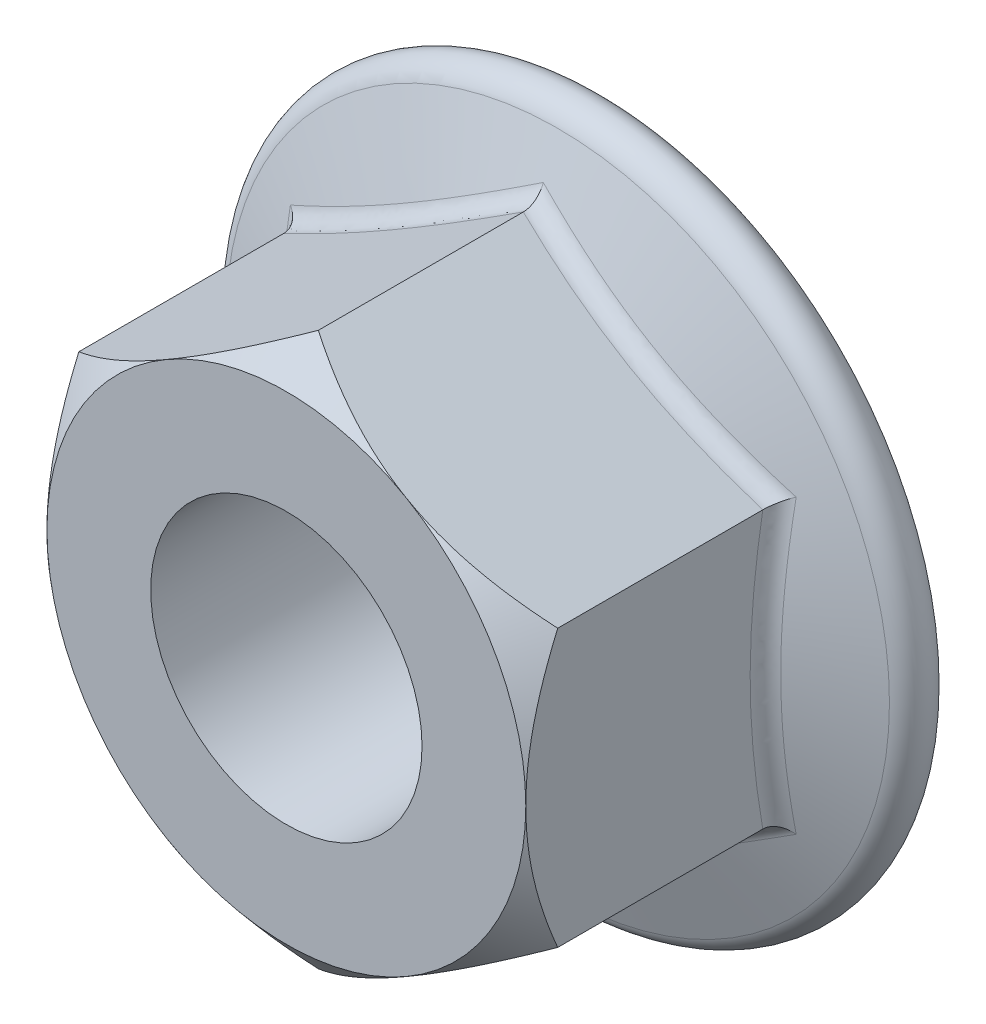
SolidWorks part; units mm, degrees
extrude "BaseNut" add sketch "BaseNutSke" against normal blind 10
sketch "BaseNutSke" plane through (0, 0, 0) normal (0, 0, 1) x (1, 0, 0)
  line L6 (7.5, 4.3301) -> (7.5, -4.3301)
  line L7 (-7.5, 4.3301) -> (-7.5, -4.3301)
  line L8 (7.5, 4.3301) -> (0, 8.6603)
  line L9 (0, 8.6603) -> (-7.5, 4.3301)
  line L10 (-7.5, -4.3301) -> (0, -8.6603)
  line L11 (0, -8.6603) -> (7.5, -4.3301)
  circle A0 centre (0, 0) radius 4.25
  dimension "Tap_drill" = 8.5
  dimension "Width_flats" = 15
  dimension "D2" = 7.5
  dimension "D3" = 7.5
  dimension "D1" = 120
  dimension "D4" = 7.5
cosmetic thread "ThreadCosmetic" parameters "Thread_major"=10
pattern_linear "ThdSchPat" [suppressed]
revolve "ThreadSchematic" [suppressed] cut sketch "ThdSchSke" angle 360 about L6
sketch "ThdSchSke" plane through (0, 0, 0) normal (0, 1, 0) x (1, 0, 0)
  line L0 (-5, 0.0254) -> (-4.25, 0.5506)
  line L1 (-4.25, 0.5506) -> (-2.125, 0.5506)
  line L2 (-2.125, 0.5506) -> (-2.125, -0.4998)
  line L3 (-2.125, -0.4998) -> (-4.25, -0.4998)
  line L4 (-4.25, -0.4998) -> (-5, 0.0254)
  line L5 (-3.175, 1.5) -> (3.175, 1.5) construction
  line L6 (0, 1.5) -> (0, -2.9874) construction
  line L7 (0, 10) -> (0, 0) construction
  dimension "Thread_major" = 10
  dimension "SideAngle" = 55
  dimension "Advance" = 1.5
  dimension "D1" = 0.0254
material "AISI 316 Нержавеющая сталь, лист (SS)"
ref_plane "Plane1" through (0, 0, 0) normal (0, 0, 1) x (1, 0, 0)
ref_plane "Plane2" through (0, 0, 0) normal (0, 1, 0) x (1, 0, 0)
ref_plane "Plane3" through (0, 0, 0) normal (1, 0, 0) x (0, 0, -1)
other "Configuration Table"
sketch "Sketch6" plane through (0, 0, 0) normal (1, 0, 0) x (0, 0, -1)
  line L0 (6.2648, 4.25) -> (8.5, 10.3912)
  line L1 (10, 4.25) -> (10, 10.1267)
  line L2 (8.5, 32.2909) -> (8.5, 10.3912) construction
  line L3 (23.7075, 10.9) -> (19.5103, 10.9) construction
  line L4 (10, 4.25) -> (6.2648, 4.25)
  line L5 (23.7075, -10.9) -> (19.5103, -10.9) construction
  line L6 (10, 4.3301) -> (10, 8.6603) construction
  line L7 (0, 0) -> (32.9582, 0) construction
  line L8 (10, -4.25) -> (6.2648, -4.25) construction
  line L9 (10, 0) -> (0, 0) construction
  arc A0 (10, 10.1267) -> (8.5, 10.3912) centre (9.2267, 10.1267) ccw
  dimension "Flange_thickness" = 1.5
  dimension "Flange_dia" = 21.8
  dimension "D2" = 20
  dimension "D1" = 8.5
revolve "Flange" add sketch "Sketch6" angle 360 about L7
sketch "Sketch3" plane through (0, 0, 0) normal (1, 0, 0) x (0, 0, -1)
  line L0 (10, 7.5) -> (9, 8.6603) construction
  line L1 (9, 8.6603) -> (9, 21.3603) construction
  line L2 (9, 21.3603) -> (22.7, 21.3603) construction
  line L3 (22.7, 21.3603) -> (22.7, 7.5) construction
  line L4 (22.7, 7.5) -> (10, 7.5) construction
  line L5 (10, 4.3301) -> (10, 8.6603) construction
  line L6 (7.87, 8.6603) -> (0, 8.6603) construction
  line L7 (0, 0) -> (38.6776, 0) construction
  line L8 (10, 0) -> (0, 0) construction
  line L9 (5, 8.6603) -> (5, 44.222) construction
  line L10 (1, 21.3603) -> (-12.7, 21.3603)
  line L11 (-12.7, 21.3603) -> (-12.7, 7.5)
  line L12 (-12.7, 7.5) -> (0, 7.5)
  line L13 (0, 7.5) -> (1, 8.6603)
  line L14 (1, 8.6603) -> (1, 21.3603)
  line L16 (7.87, 8.6603) -> (0, 8.6603) construction
  dimension "D2" = 1
  dimension "D4" = 12.7
  dimension "D3" = 12.7
  dimension "D5" = 5
revolve "Double-Chamfer" cut sketch "Sketch3" angle 360 about L7
fillet "FlangeFillet" radius 0.6 6 edges
sketch "Sketch5" plane through (0, 0, 0) normal (1, 0, 0) x (0, 0, -1)
  line L0 (35.3492, 5) -> (34.7715, 4.175)
  line L1 (35.4, 5) -> (35.3492, 5)
  line L2 (35.4, 5) -> (35.4, 4.175)
  line L3 (35.4, 4.175) -> (34.7715, 4.175)
  line L6 (-50.8, 5) -> (-50.7492, 5)
  line L7 (-50.7492, 5) -> (-50.1715, 4.175)
  line L9 (-50.1715, 4.175) -> (-50.8, 4.175)
  line L10 (-50.8, 4.175) -> (-50.8, 5)
  line L11 (25.0375, 0) -> (38.388, 0) construction
  line L12 (10, 0) -> (0, 0) construction
  dimension "D1" = 35
  dimension "ThreadMajor" = 5
  dimension "Offset1" = 35.4
revolve "EndChamfer" [suppressed] cut sketch "Sketch5" angle 360 about L11
equation "\"D2@BaseNutSke\" = \"Width_flats@BaseNutSke\" / 2"
equation "\"D3@BaseNutSke\" = \"Width_flats@BaseNutSke\" / 2"
equation "\"D1@Sketch3\" = \"Width_flats@BaseNutSke\" /2"
equation "\"D2@Sketch3\" = \"Thread_major@ThreadCosmetic\" *.1"
equation "\"D4@BaseNutSke\" = \"D3@BaseNutSke\""
equation "\"Thread_major@ThdSchSke\" = \"Thread_major@ThreadCosmetic\""
equation "\"Tap_Drill@ThdSchSke\" = \"Tap_drill@BaseNutSke\""
equation "\"OverCut@ThdSchSke\" = \"Tap_Drill@ThdSchSke\" * 0.5"
equation "\"Num_threads@ThdSchPat\" = int(  ( \"Thickness@BaseNut\" - 0.0508 ) / \"Advance@ThdSchSke\" + 0.999 )  + 1"
equation "\"Advance@ThdSchPat\" = ( \"Thickness@BaseNut\" - 0.0508 ) /  (\"Num_threads@ThdSchPat\" - 1) 'relax it"
equation "' \"Num_threads@ThdSchPat\" = \"Num_threads@ThdSchPat\" - sgn( \"Num_threads@ThdSchPat\" - 1) '---chamfered tips only---"
equation "\"ThreadMajor@Sketch5\" = \"Thread_major@ThreadCosmetic\" * 0.5"
equation "\"ChamferDepth@Sketch5\" = (\"Thread_major@ThreadCosmetic\" - \"Tap_drill@BaseNutSke\") * 0.55"
equation "\"Offset1@Sketch5\" = \"Thickness@BaseNut\" + 0.0254"
equation "\"Offset2@Sketch5\" = \"Offset1@Sketch5\" + 0.0508"
equation "\"D1@Sketch6\" = \"Tap_drill@BaseNutSke\""
equation "\"D5@Sketch3\" = \"Thickness@BaseNut\" / 2"
